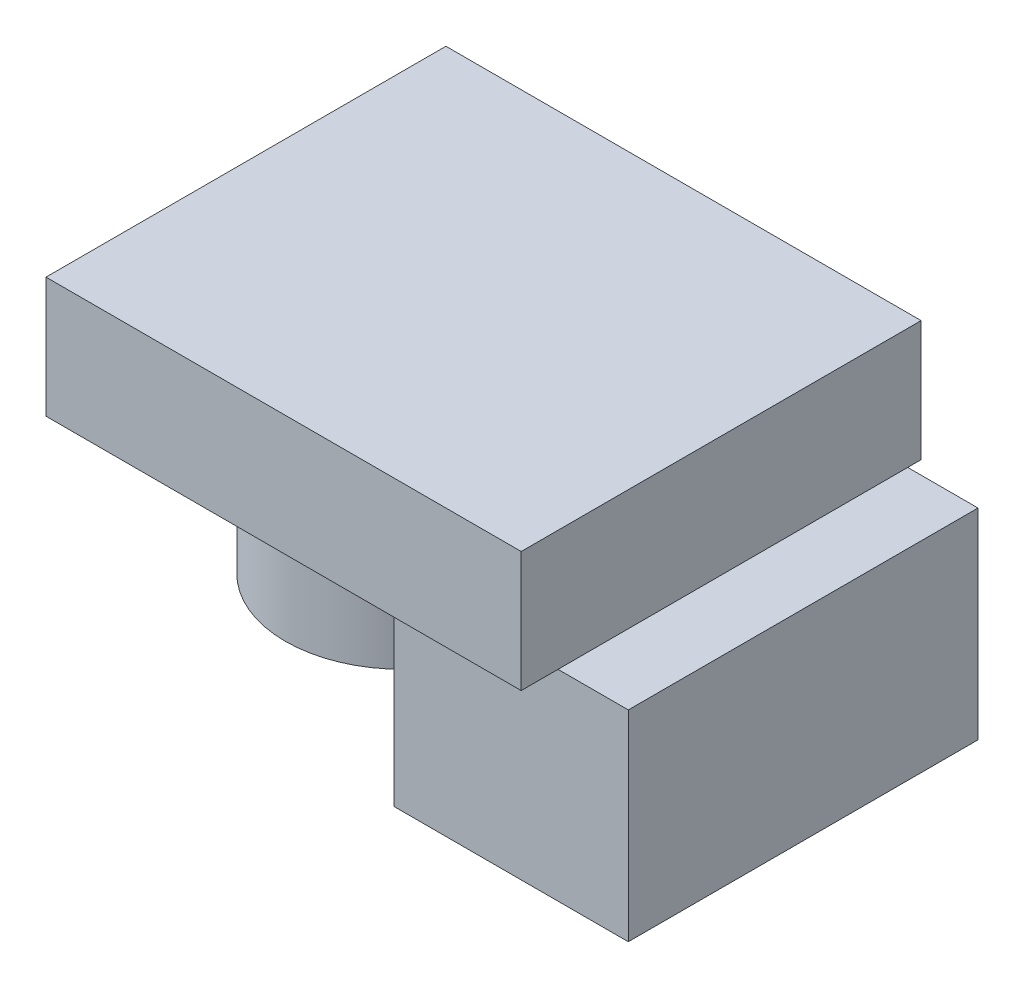
SolidWorks part; units mm, degrees
ref_plane "Front Plane" through (0, 0, 0) normal (0, 0, 1) x (1, 0, 0)
ref_plane "Top Plane" through (0, 0, 0) normal (0, 1, 0) x (1, 0, 0)
ref_plane "Right Plane" through (0, 0, 0) normal (1, 0, 0) x (0, 0, -1)
sketch "Sketch3" plane through (0, 0, 0) normal (0, 1, 0) x (1, 0, 0)
  circle A0 centre (0, 0) radius 3.5
  point P2 (0, 0)
  point P4 (0, 0)
  dimension "D1" = 7
extrude "Boss-Extrude2" add sketch "Sketch3" along normal blind 5.5
sketch "Sketch1" plane through (0, 5.5, 0) normal (0, 1, 0) x (1, 0, 0)
  line L1 (-3.9, 5.2) -> (10.3, 5.2)
  line L2 (-3.9, 5.2) -> (-3.9, -6.75)
  line L3 (-3.9, -6.75) -> (10.3, -6.75)
  line L4 (10.3, 5.2) -> (10.3, -6.75)
  circle A0 centre (0, 0) radius 3.5 construction
  dimension "D3" = 3.9
  dimension "D4" = 6.75
  dimension "D1" = 5.2
  dimension "D2" = 14.2
extrude "Boss-Extrude3" add sketch "Sketch1" along normal blind 3.6
sketch "Sketch4" plane through (0, 5.5, 0) normal (0, -1, 0) x (1, 0, 0)
  line L0 (10.3, -5.2) -> (-3.9, -5.2) construction
  line L1 (5.4, 5.65) -> (12.4, 5.65)
  line L2 (5.4, 5.65) -> (5.4, -4.8)
  line L3 (5.4, -4.8) -> (12.4, -4.8)
  line L4 (12.4, 5.65) -> (12.4, -4.8)
  line L5 (-3.9, 6.75) -> (10.3, 6.75) construction
  line L6 (10.3, 6.75) -> (10.3, -5.2) construction
  dimension "D1" = 0.4
  dimension "D2" = 1.1
  dimension "D3" = 7
  dimension "D4" = 2.1
extrude "Boss-Extrude4" add sketch "Sketch4" along normal blind 6
